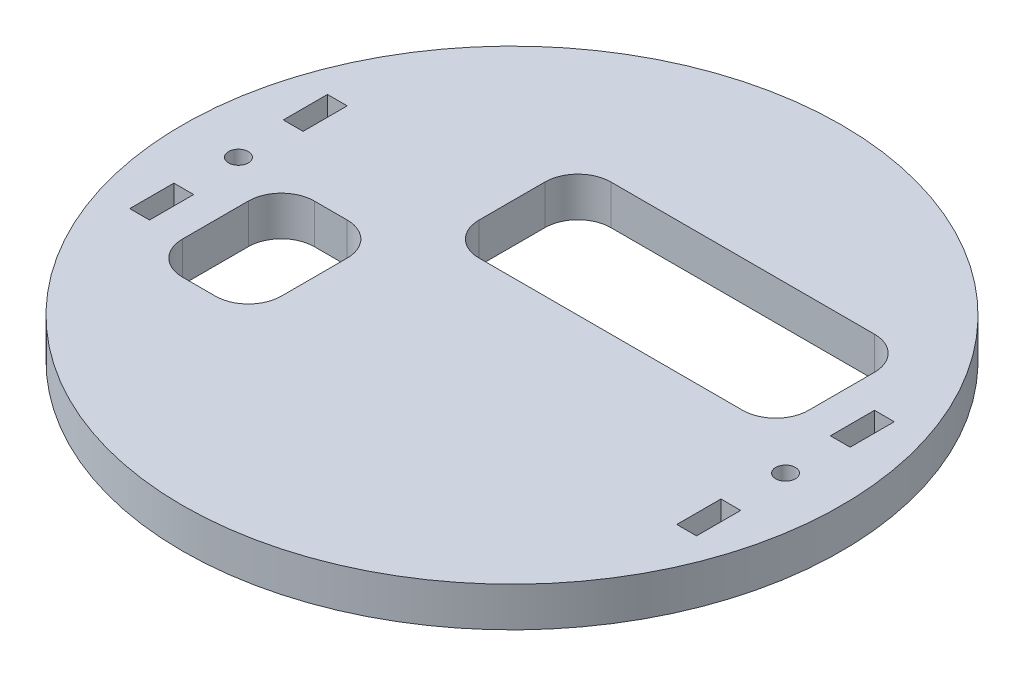
SolidWorks part; units mm, degrees
ref_plane "Front Plane" through (0, 0, 0) normal (0, 0, 1) x (1, 0, 0)
ref_plane "Top Plane" through (0, 0, 0) normal (0, 1, 0) x (1, 0, 0)
ref_plane "Right Plane" through (0, 0, 0) normal (1, 0, 0) x (0, 0, -1)
sketch "Sketch2" plane through (0, 0, 0) normal (0, 1, 0) x (1, 0, 0)
  line L0 (-8.4172, 8.3592) -> (26.5828, 8.3592) construction
  line L1 (-8.4172, 58.3592) -> (-8.4172, -41.6408) construction
  line L2 (-8.4172, 8.3592) -> (-43.4172, 8.3592) construction
  line L3 (-48.4172, 8.3592) -> (-48.4172, 16.6592) construction
  line L4 (-48.4172, 16.6592) -> (-48.4172, 23.3592)
  line L5 (-48.4172, 23.3592) -> (-51.4172, 23.3592)
  line L6 (-51.4172, 23.3592) -> (-51.4172, 16.6592)
  line L7 (-48.4172, 0.0592) -> (-48.4172, -6.6408)
  line L8 (-48.4172, 8.3592) -> (-48.4172, 0.0592) construction
  line L9 (-48.4172, 0.0592) -> (-51.4172, 0.0592)
  line L10 (-48.4172, -6.6408) -> (-51.4172, -6.6408)
  line L11 (-51.4172, -6.6408) -> (-51.4172, 0.0592)
  line L12 (-51.4172, 16.6592) -> (-48.4172, 16.6592)
  line L13 (31.5828, 8.3592) -> (31.5828, 16.6592) construction
  line L14 (31.5828, 16.6592) -> (31.5828, 23.3592)
  line L15 (31.5828, 23.3592) -> (34.5828, 23.3592)
  line L16 (34.5828, 23.3592) -> (34.5828, 16.6592)
  line L17 (34.5828, 16.6592) -> (31.5828, 16.6592)
  line L18 (31.5828, 8.3592) -> (31.5828, 0.0592) construction
  line L19 (31.5828, 0.0592) -> (34.5828, 0.0592)
  line L20 (34.5828, 0.0592) -> (34.5828, -6.6408)
  line L21 (34.5828, -6.6408) -> (31.5828, -6.6408)
  line L22 (31.5828, -6.6408) -> (31.5828, 0.0592)
  line L23 (21.5828, 33.3592) -> (-18.4172, 33.3592)
  line L24 (-23.4172, 28.3592) -> (-23.4172, 18.3592)
  line L25 (-18.4172, 13.3592) -> (21.5828, 13.3592)
  line L26 (-33.4172, 8.3592) -> (-38.4172, 8.3592)
  line L27 (26.5828, 23.3592) -> (26.5828, 8.3592) construction
  line L28 (-38.4172, -11.6408) -> (-33.4172, -11.6408)
  line L29 (26.5828, 18.3592) -> (26.5828, 28.3592)
  line L30 (-28.4172, -6.6408) -> (-28.4172, 3.3592)
  line L31 (-43.4172, 3.3592) -> (-43.4172, -6.6408)
  circle A0 centre (-8.4172, 8.3592) radius 50
  circle A1 centre (33.0828, 8.3592) radius 1.5
  circle A2 centre (-49.9172, 8.3592) radius 1.5
  arc A3 (-18.4172, 33.3592) -> (-23.4172, 28.3592) centre (-18.4172, 28.3592) ccw
  arc A4 (-23.4172, 18.3592) -> (-18.4172, 13.3592) centre (-18.4172, 18.3592) ccw
  arc A5 (-43.4172, -6.6408) -> (-38.4172, -11.6408) centre (-38.4172, -6.6408) ccw
  arc A6 (-33.4172, -11.6408) -> (-28.4172, -6.6408) centre (-33.4172, -6.6408) ccw
  arc A7 (21.5828, 13.3592) -> (26.5828, 18.3592) centre (21.5828, 18.3592) ccw
  arc A8 (26.5828, 28.3592) -> (21.5828, 33.3592) centre (21.5828, 28.3592) ccw
  arc A9 (-28.4172, 3.3592) -> (-33.4172, 8.3592) centre (-33.4172, 3.3592) ccw
  arc A10 (-38.4172, 8.3592) -> (-43.4172, 3.3592) centre (-38.4172, 3.3592) ccw
  dimension "D1" = 40
extrude "Boss-Extrude2" add sketch "Sketch2" along normal blind 6
